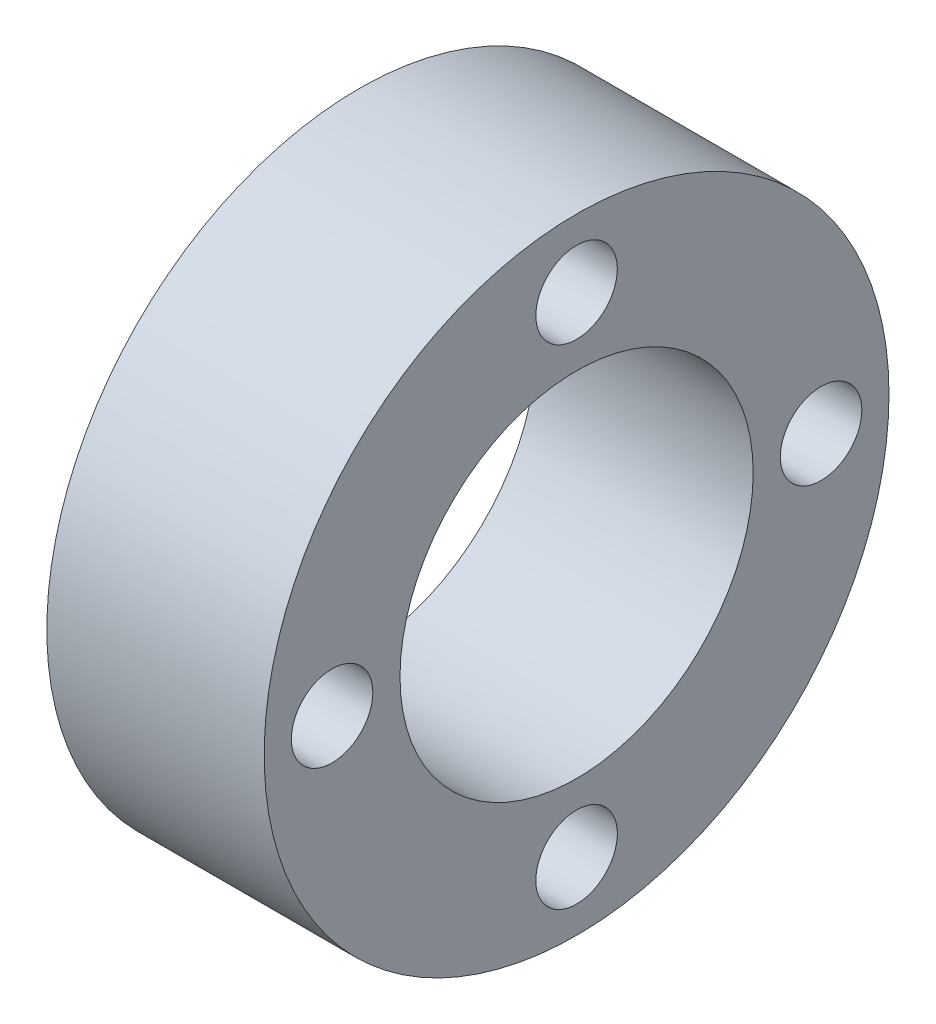
SolidWorks part; units mm, degrees
ref_plane "前视基准面" through (0, 0, 0) normal (0, 0, 1) x (1, 0, 0)
ref_plane "上视基准面" through (0, 0, 0) normal (0, 1, 0) x (1, 0, 0)
ref_plane "右视基准面" through (0, 0, 0) normal (1, 0, 0) x (0, 0, -1)
sketch "草图1" plane through (0, 0, 0) normal (1, 0, 0) x (0, 0, -1)
  circle A0 centre (0, 0) radius 11.5
  circle A1 centre (0, 0) radius 6.5
  dimension "D1" = 23
  dimension "D2" = 13
extrude "拉伸1" add sketch "草图1" along normal blind 8
cosmetic thread "装饰螺纹线1" parameters "D2"=22.5
sketch "草图2" plane through (8, 0, 0) normal (1, 0, 0) x (0, 0, -1)
  circle A0 centre (0, 9) radius 1.5
  dimension "D2" = 3
  dimension "D1" = 9
extrude "拉伸2" cut sketch "草图2" against normal blind 3
pattern_circular "阵列(圆周)1" count 4 over 360 about axis through (0, 0, 0) along (1, 0, 0) of "拉伸2"
